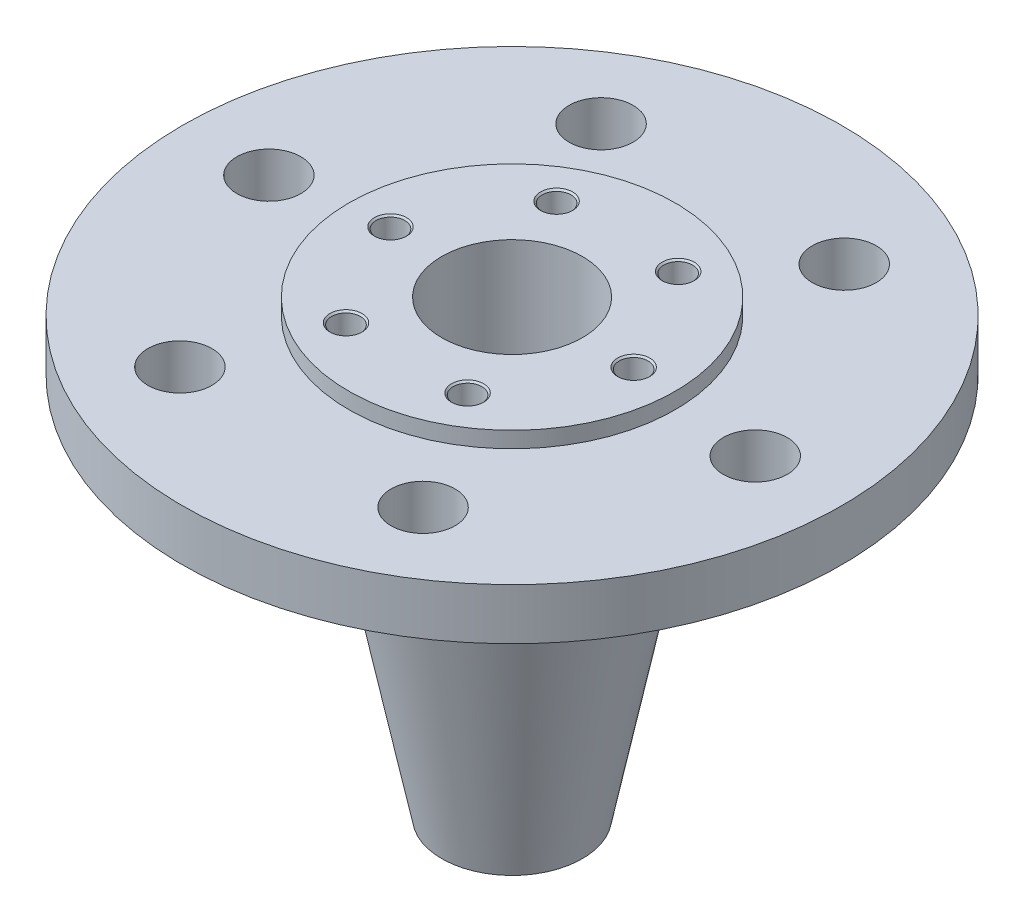
SolidWorks part; units mm, degrees
ref_plane "Front Plane" through (0, 0, 0) normal (0, 0, 1) x (1, 0, 0)
ref_plane "Top Plane" through (0, 0, 0) normal (0, 1, 0) x (1, 0, 0)
ref_plane "Right Plane" through (0, 0, 0) normal (1, 0, 0) x (0, 0, -1)
sketch "Sketch1" plane through (0, 0, 0) normal (0, 0, 1) x (1, 0, 0)
  line L0 (22, 0) -> (44, 110)
  line L2 (44, 110) -> (54, 110)
  line L3 (54, 110) -> (54, 120)
  line L4 (54, 120) -> (103, 120)
  line L5 (103, 120) -> (103, 136)
  line L6 (103, 136) -> (51, 136)
  line L7 (51, 136) -> (51, 141)
  line L8 (51, 141) -> (0, 141)
  line L9 (0, 141) -> (0, 0)
  line L10 (0, 0) -> (22, 0)
  point P2 (0, 0)
  dimension "D1" = 22
  dimension "D2" = 44
  dimension "D3" = 51
  dimension "D4" = 103
  dimension "D5" = 5
  dimension "D6" = 16
  dimension "D7" = 10
  dimension "D8" = 54
  dimension "D9" = 120
revolve "Revolve1" add sketch "Sketch1" angle 360 about L9
sketch "Sketch2" plane through (0, 0, 0) normal (0, 0, 1) x (1, 0, 0)
  line L0 (0, 0) -> (11.4143, 0)
  line L1 (-22, 0) -> (22, 0) construction
  line L2 (11.4143, 0) -> (11.4143, 38)
  line L3 (11.4143, 38) -> (16, 42.5857)
  line L4 (16, 42.5857) -> (16, 54.753)
  line L5 (16, 54.753) -> (11, 58)
  line L6 (11, 58) -> (11, 75)
  line L7 (11, 75) -> (22, 86)
  line L8 (22, 86) -> (22, 141)
  line L9 (51, 141) -> (-51, 141) construction
  line L10 (22, 141) -> (0, 141)
  line L11 (0, 141) -> (0, 0)
  line L12 (16, 54.753) -> (-10.2625, 54.753) construction
  line L13 (11.4143, 38) -> (4.4662, 38) construction
  point P15 (4.4662, 38)
  dimension "D1" = 11.4143
  dimension "D2" = 11
  dimension "D3" = 20
  dimension "D4" = 38
  dimension "D5" = 22
  dimension "D6" = 135
  dimension "D7" = 33
  dimension "D8" = 55
  dimension "D9" = 16
revolve "Cut-Revolve1" cut sketch "Sketch2" angle 360 about L11
hole_wizard "Hole1" positions "Sketch6" profile "Sketch7" legacy
sketch "Sketch6" plane through (0, 136, 0) normal (0, 1, 0) x (1, 0, 0)
  point P0 (76, 0)
  point P4 (0, 0)
  dimension "D1" = 76
sketch "Sketch7" plane through (76, 136, 0) normal (1, 0, 0) x (0, 0, 1)
  line L0 (0, 0) -> (0, 16)
  line L1 (0, 16) -> (10, 16)
  line L2 (10, 16) -> (10, 0)
  line L3 (10, 0) -> (0, 0)
  line L4 (0, 110) -> (0, -10) construction
  dimension "Diameter" = 20
  dimension "Depth" = 16
pattern_circular "CirPattern1" count 6 over 360 about axis through (0, 0, 0) along (0, 1, 0) of "Hole1"
hole_wizard "M10x1.0 Tapped Hole5" positions "Sketch8" profile "Sketch9" tap size "M10x1.0" standard "ANSI Metric"
sketch "Sketch8" plane through (0, 141, 0) normal (0, 1, 0) x (1, 0, 0)
  point P0 (38, 0)
  dimension "D1" = 38
sketch "Sketch9" plane through (38, 141, 0) normal (1, 0, 0) x (0, 0, 1)
  line L0 (0, 0) -> (0, 17.7039)
  line L1 (0, 17.7039) -> (4.5, 15)
  line L2 (4.5, 15) -> (4.5, 0.525)
  line L3 (4.5, 0.525) -> (5.025, 0)
  line L5 (5.025, 0) -> (0, 0)
  line L6 (-4.5, 0.525) -> (-5.025, 0) construction
  line L10 (0, 17.7039) -> (-4.5, 15) construction
  line L11 (0, -6.35) -> (0, 107.95) construction
  dimension "Tap Drill Dia." = 9
  dimension "Tap Drill Depth" = 15
  dimension "Near C'Sink Dia." = 10.05
  dimension "Near C'Sink Angle" = 90
  dimension "Drill Angle" = 118
cosmetic thread "Hole Thread2" parameters "D1"=18, "D2"=10
pattern_circular "CirPattern2" count 6 over 360 about axis through (0, 0, 0) along (0, 1, 0) of "M10x1.0 Tapped Hole5"
cosmetic thread "Hole Thread3" parameters "D1"=18, "D2"=10
cosmetic thread "Hole Thread4" parameters "D1"=18, "D2"=10
cosmetic thread "Hole Thread5" parameters "D1"=18, "D2"=10
cosmetic thread "Hole Thread6" parameters "D1"=18, "D2"=10
cosmetic thread "Hole Thread7" parameters "D1"=18, "D2"=10
